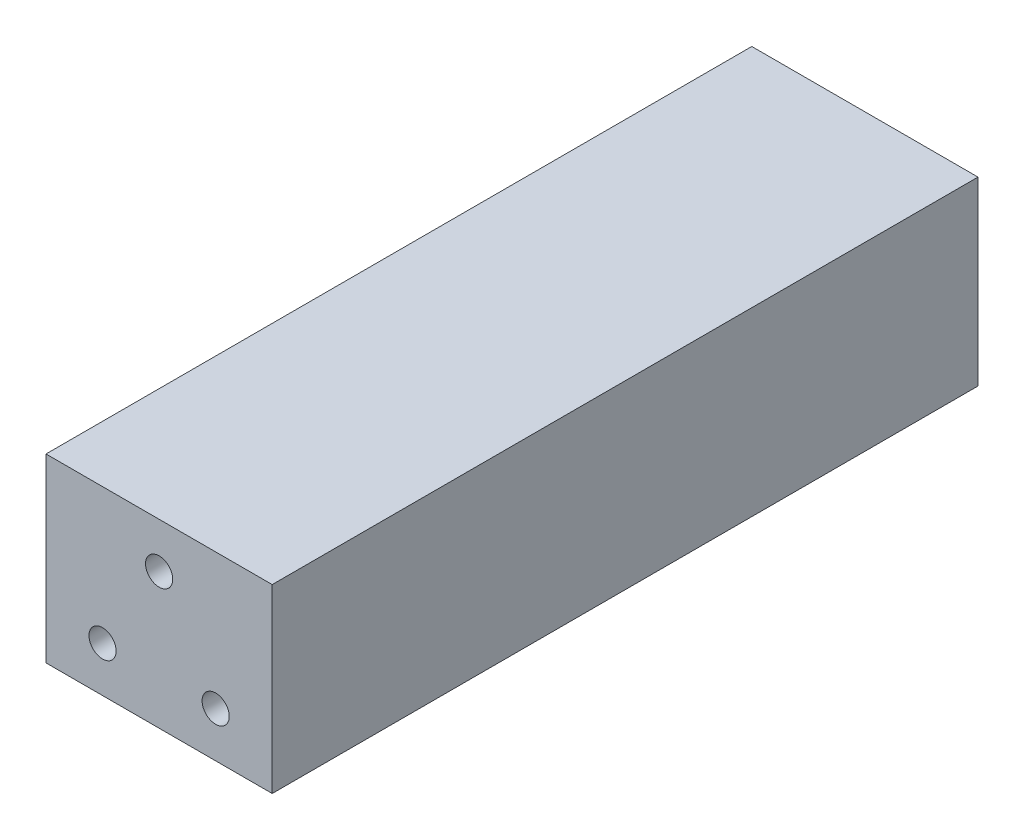
SolidWorks part; units mm, degrees
ref_plane "Front Plane" through (0, 0, 0) normal (0, 0, 1) x (1, 0, 0)
ref_plane "Top Plane" through (0, 0, 0) normal (0, 1, 0) x (1, 0, 0)
ref_plane "Right Plane" through (0, 0, 0) normal (1, 0, 0) x (0, 0, -1)
sketch "Sketch1" plane through (0, 0, 0) normal (0, 0, 1) x (1, 0, 0)
  line L1 (0, 0) -> (25, 0)
  line L2 (0, 0) -> (0, -20)
  line L3 (0, -20) -> (25, -20)
  line L4 (25, 0) -> (25, -20)
  dimension "D1" = 25
  dimension "D2" = 20
extrude "Boss-Extrude2" add sketch "Sketch1" along normal blind 78
sketch "Sketch3" plane through (0, 0, 78) normal (0, 0, 1) x (1, 0, 0)
  circle A1 centre (6.25, -15) radius 1.5
  circle A2 centre (12.5, -5) radius 1.5
  circle A3 centre (18.75, -15) radius 1.5
  dimension "D1" = 3
  dimension "D2" = 3
  dimension "D3" = 3
extrude "Cut-Extrude2" cut sketch "Sketch3" against normal blind 10
sketch "Sketch6" plane through (0, 0, 0) normal (0, 0, -1) x (-1, 0, 0)
  circle A0 centre (-12.5, -5) radius 1.4855
  circle A1 centre (-6.25, -15) radius 1.5474
  circle A2 centre (-18.75, -15) radius 1.4946
extrude "Cut-Extrude3" cut sketch "Sketch6" against normal blind 10
